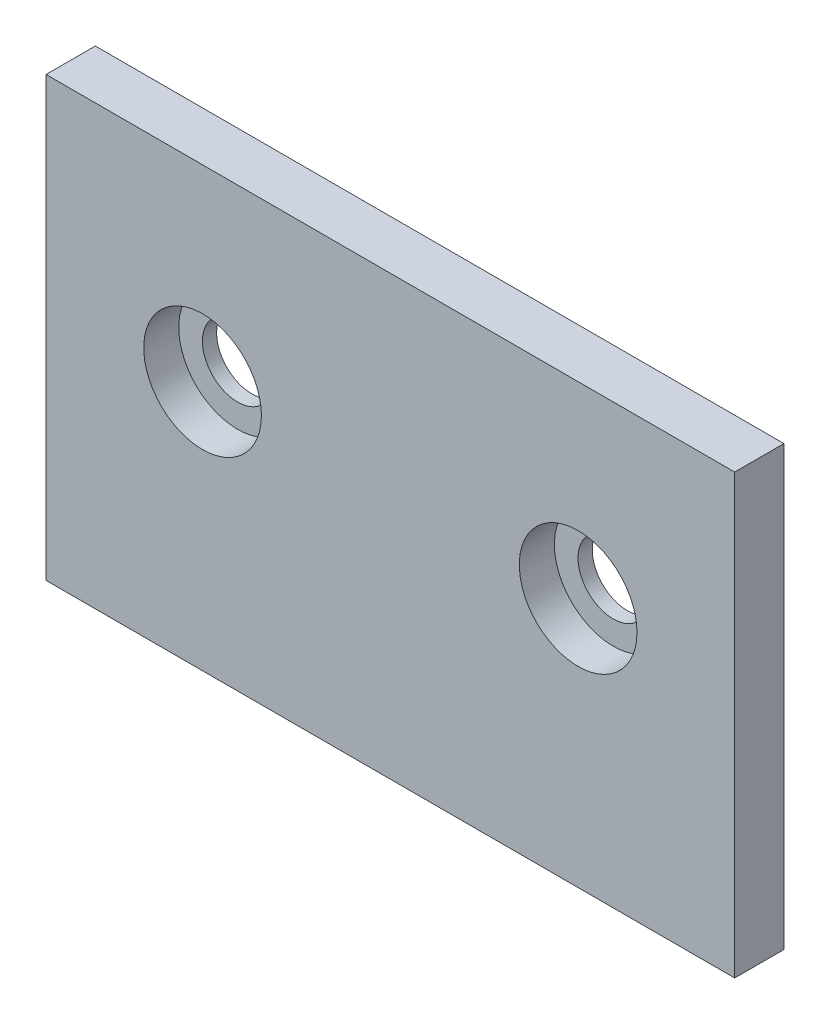
SolidWorks part; units mm, degrees
ref_plane "Alzado" through (0, 0, 0) normal (0, 0, 1) x (1, 0, 0)
ref_plane "Planta" through (0, 0, 0) normal (0, 1, 0) x (1, 0, 0)
ref_plane "Vista lateral" through (0, 0, 0) normal (1, 0, 0) x (0, 0, -1)
sketch "Croquis1" plane through (0, 0, 0) normal (0, 0, 1) x (1, 0, 0)
  line L1 (-34.925, 22.225) -> (34.925, 22.225)
  line L2 (-34.925, 22.225) -> (-34.925, -22.225)
  line L3 (-34.925, -22.225) -> (34.925, -22.225)
  line L4 (34.925, 22.225) -> (34.925, -22.225)
  line L5 (-34.925, 22.225) -> (34.925, -22.225) construction
  line L6 (-34.925, -22.225) -> (34.925, 22.225) construction
  point P0 (0, 0)
  dimension "D1" = 44.45
  dimension "D2" = 69.85
extrude "Saliente-Extruir1" add sketch "Croquis1" against normal blind 5
hole_wizard "Refrentado para tornillo con cabeza hueca de 1/42" positions "Croquis4" profile "Croquis5" counterbore size "1/4" standard "Ansi Inch"
sketch "Croquis4" plane through (0, 0, 0) normal (0, 0, 1) x (1, 0, 0)
  line L0 (0, 22.225) -> (0, -22.225) construction
  line L1 (34.925, 22.225) -> (-34.925, 22.225) construction
  line L2 (-34.925, -22.225) -> (34.925, -22.225) construction
  point P0 (-19.05, 3.175)
  point P2 (19.05, 3.175)
  point P12 (0, 0)
  point P13 (0, 0)
  dimension "D1" = 38.1
  dimension "D2" = 25.4
sketch "Croquis5" plane through (-19.05, 3.175, 0) normal (1, 0, 0) x (0, -1, 0)
  line L0 (0, 0) -> (0, 26.1458)
  line L1 (0, 26.1458) -> (3.5712, 24)
  line L2 (3.5712, 24) -> (3.5712, 3.556)
  line L3 (3.5712, 3.556) -> (5.969, 3.556)
  line L4 (5.969, 3.556) -> (5.969, 0)
  line L5 (5.969, 0) -> (0, 0)
  line L10 (0, 26.1458) -> (-3.5712, 24) construction
  line L11 (0, -6.35) -> (0, 107.95) construction
  dimension "Diámetro de taladro" = 7.1425
  dimension "Profundidad de taladro" = 24
  dimension "Diámetro de refrentado" = 11.938
  dimension "Profundidad de refrentado" = 3.556
  dimension "Ángulo de perforador" = 118
